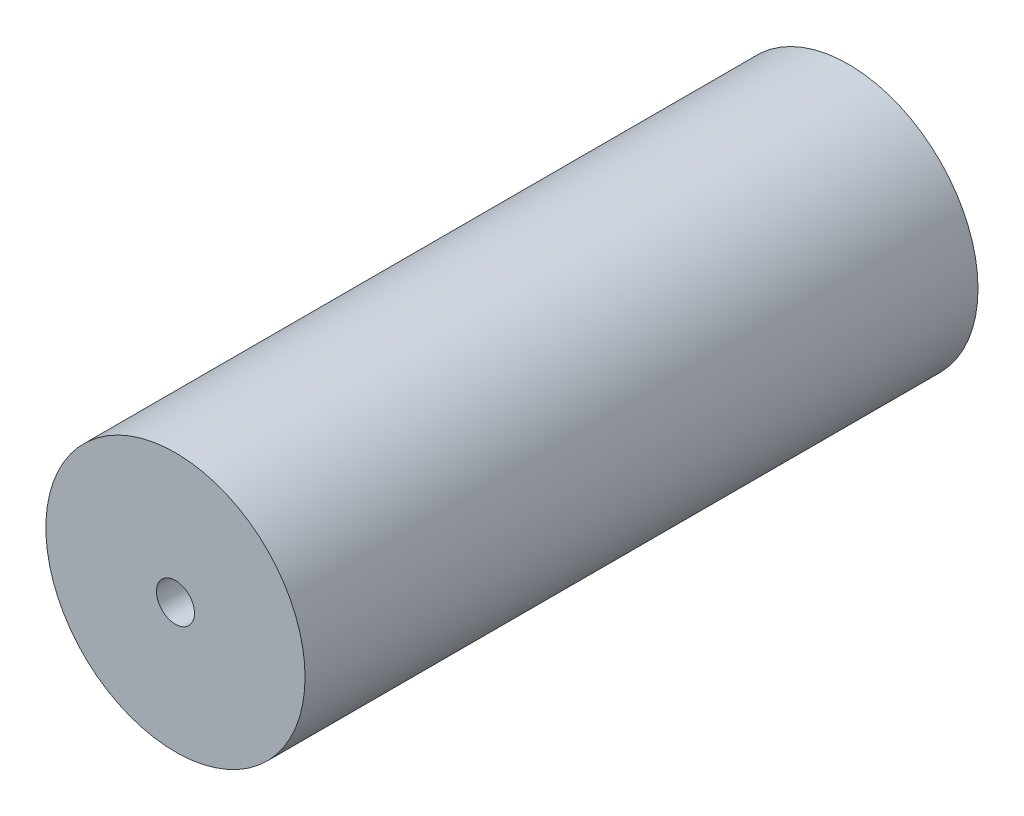
SolidWorks part; units mm, degrees
ref_plane "Front Plane" through (0, 0, 0) normal (0, 0, 1) x (1, 0, 0)
ref_plane "Top Plane" through (0, 0, 0) normal (0, 1, 0) x (1, 0, 0)
ref_plane "Right Plane" through (0, 0, 0) normal (1, 0, 0) x (0, 0, -1)
sketch "Sketch2" plane through (0, 0, 0) normal (0, 0, 1) x (1, 0, 0)
  circle A0 centre (0, 0) radius 26
  dimension "D1" = 52
extrude "Boss-Extrude1" add sketch "Sketch2" along normal blind 135 contours A0
sketch "Sketch3" plane through (0, 0, 0) normal (0, 0, -1) x (-1, 0, 0)
  circle A0 centre (0, 0) radius 3.815
  dimension "D1" = 7.63
extrude "Cut-Extrude1" cut sketch "Sketch3" against normal blind 135
sketch "Sketch5" plane through (0, 0, 0) normal (0, 0, -1) x (-1, 0, 0)
  circle A0 centre (0, 0) radius 18.5
  dimension "D1" = 37
extrude "Cut-Extrude2" cut sketch "Sketch5" against normal blind 30
